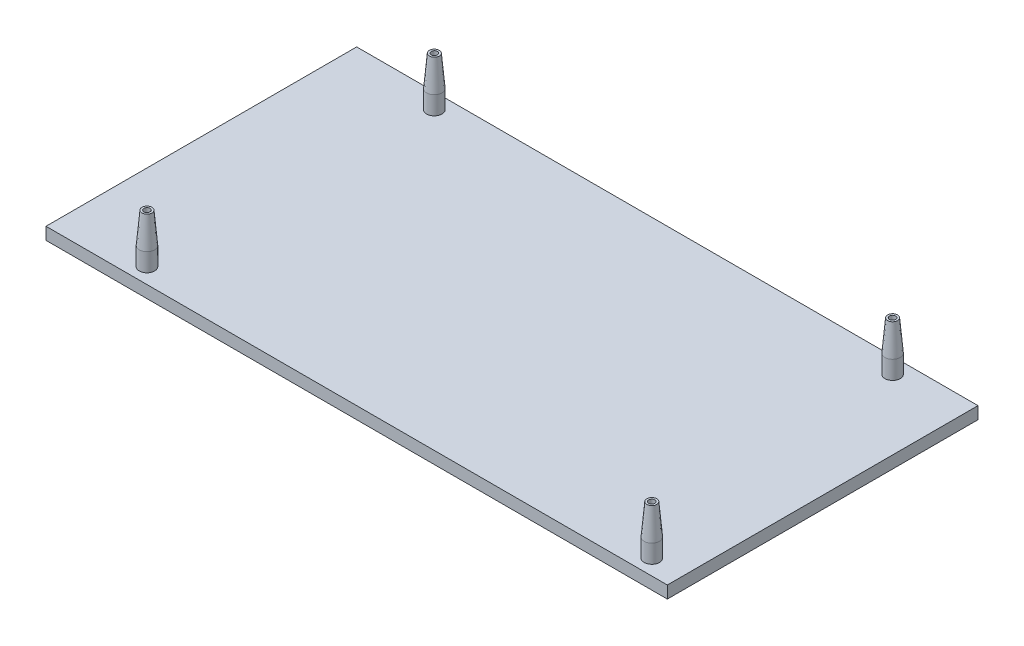
SolidWorks part; units mm, degrees
ref_plane "Front Plane" through (0, 0, 0) normal (0, 0, 1) x (1, 0, 0)
ref_plane "Top Plane" through (0, 0, 0) normal (0, 1, 0) x (1, 0, 0)
ref_plane "Right Plane" through (0, 0, 0) normal (1, 0, 0) x (0, 0, -1)
sketch "Sketch1" plane through (0, 0, 0) normal (0, 1, 0) x (1, 0, 0)
  line L0 (-33.2658, 21.7003) -> (83.5965, 21.7003) construction
  line L1 (-26.3612, 24.2403) -> (75.2388, 24.2403)
  line L2 (-26.3612, 24.2403) -> (-26.3612, -26.5597)
  line L3 (-26.3612, -26.5597) -> (75.2388, -26.5597)
  line L4 (75.2388, 24.2403) -> (75.2388, -26.5597)
  line L5 (-38.428, -24.0197) -> (87.8635, -24.0197) construction
  circle A0 centre (-11.1212, 21.7003) radius 0.5
  circle A1 centre (-12.3912, -24.0197) radius 0.5
  circle A2 centre (63.8088, 21.7003) radius 0.5
  circle A3 centre (70.1588, -24.0197) radius 0.5
  dimension "D4" = 1
  dimension "D6" = 1
  dimension "D11" = 1
  dimension "D12" = 1
  dimension "D1" = 50.8
  dimension "D2" = 101.6
  dimension "D3" = 2.54
  dimension "D5" = 15.24
  dimension "D7" = 13.97
  dimension "D8" = 2.54
  dimension "D9" = 90.17
  dimension "D10" = 96.52
extrude "Boss-Extrude1" add sketch "Sketch1" along normal blind 2
sketch "Sketch2" plane through (0, 2, 0) normal (0, 1, 0) x (1, 0, 0)
  circle A0 centre (-11.1212, 21.7003) radius 0.5
  circle A1 centre (-11.1212, 21.7003) radius 1.25
  circle A2 centre (-12.3912, -24.0197) radius 0.5
  circle A3 centre (-12.3912, -24.0197) radius 1.25
  circle A4 centre (70.1588, -24.0197) radius 0.5
  circle A5 centre (70.1588, -24.0197) radius 1.25
  circle A6 centre (63.8088, 21.7003) radius 0.5
  circle A7 centre (63.8088, 21.7003) radius 1.25
  circle A8 centre (70.1588, -24.0197) radius 0.5 construction
  circle A9 centre (63.8088, 21.7003) radius 0.5 construction
  circle A10 centre (-11.1212, 21.7003) radius 0.5 construction
  circle A11 centre (-12.3912, -24.0197) radius 0.5 construction
  dimension "D1" = 2.5
  dimension "D2" = 2.5
  dimension "D3" = 2.5
  dimension "D4" = 2.5
extrude "Boss-Extrude2" add sketch "Sketch2" along normal blind 8
chamfer "Chamfer1" distance 5 angle 5 4 edges at (-11.1212, 10, -20.4503) (63.8088, 10, -20.4503) (70.1588, 10, 25.2697) (-12.3912, 10, 25.2697)
